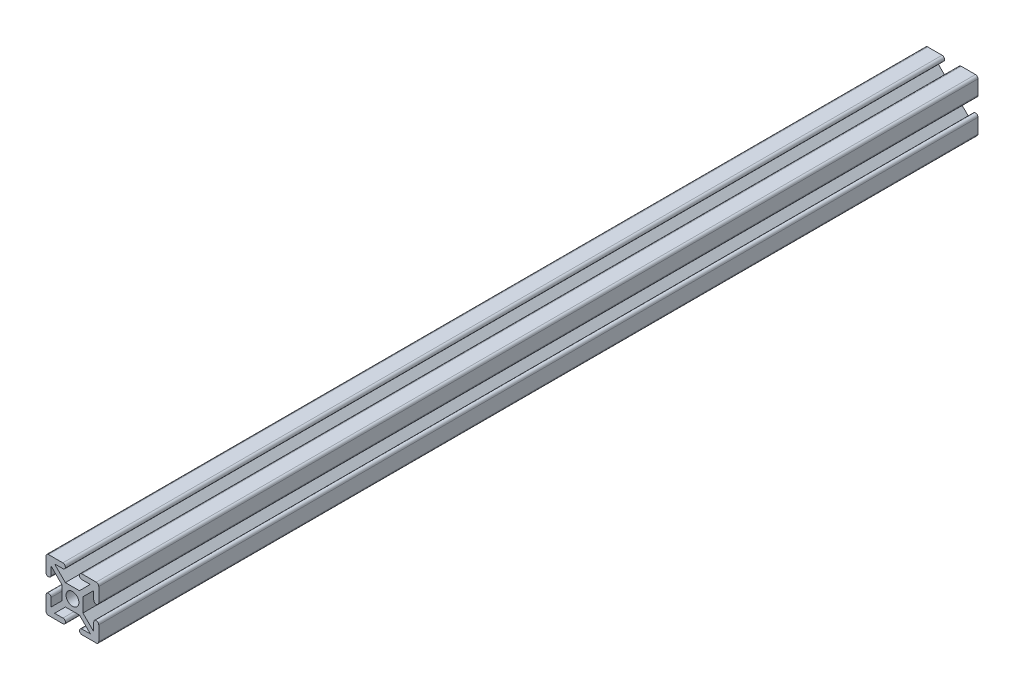
SolidWorks part; units mm, degrees
material "Aleación 6061"
ref_plane "Alzado" through (0, 0, 0) normal (0, 0, 1) x (1, 0, 0)
ref_plane "Planta" through (0, 0, 0) normal (0, 1, 0) x (1, 0, 0)
ref_plane "Vista lateral" through (0, 0, 0) normal (1, 0, 0) x (0, 0, -1)
sketch "Croquis1" plane through (0, 0, 0) normal (0, 0, 1) x (1, 0, 0)
  line L0 (-6.9113, -9.1825) -> (-6.9113, -7.7575) construction
  line L1 (12.1416, -25.3325) -> (16.8666, -25.3325)
  line L2 (-8.3363, 0.3925) -> (-8.3363, -7.7575)
  line L3 (-6.9113, 1.8175) -> (1.2387, 1.8175)
  line L4 (12.0887, 1.8175) -> (20.2387, 1.8175)
  line L5 (-3.4334, -25.3325) -> (1.2916, -25.3325)
  line L6 (0.6637, -9.1825) -> (0.6637, -17.1825)
  line L7 (-8.2834, -18.6075) -> (-8.2834, -26.7575)
  line L8 (-6.8849, -28.1561) -> (1.2916, -28.1825)
  line L9 (21.6637, 0.3925) -> (21.6637, -7.6538)
  line L10 (-5.4863, -3.0325) -> (-5.4863, -7.7575)
  line L11 (21.6637, -18.5038) -> (21.6637, -26.7575)
  line L12 (2.6637, 0.3925) -> (1.2387, 0.3925) construction
  line L13 (12.1416, -28.1825) -> (20.2387, -28.1825)
  line L14 (-3.4863, -1.0325) -> (1.2387, -1.0325)
  line L15 (-5.4863, -18.6075) -> (-5.4863, -23.3325)
  line L16 (10.6637, 0.3925) -> (12.0887, 0.3925) construction
  line L17 (12.0887, -1.0325) -> (16.8137, -1.0325)
  line L18 (20.2387, -9.0788) -> (20.2387, -7.6538) construction
  line L19 (2.6637, -7.1825) -> (-3.4863, -1.0325)
  line L20 (18.8137, -3.0325) -> (18.8137, -7.6538)
  line L21 (20.2387, -17.0788) -> (20.2387, -18.5038) construction
  line L22 (0.6637, -9.1825) -> (-5.4863, -3.0325)
  line L23 (18.8137, -18.5038) -> (18.8137, -23.3325)
  line L24 (10.7166, -26.7575) -> (12.1416, -26.7575) construction
  line L25 (0.6637, -17.1825) -> (-5.4863, -23.3325)
  line L26 (2.6637, -7.1825) -> (10.6637, -7.1825)
  line L27 (10.6637, -7.1825) -> (16.8137, -1.0325)
  line L28 (-6.8849, -17.1825) -> (-6.8849, -18.6075) construction
  line L29 (-3.4334, -25.3325) -> (2.7166, -19.1825)
  line L30 (2.7166, -19.1825) -> (10.7166, -19.1825)
  line L31 (10.7166, -19.1825) -> (16.8666, -25.3325)
  line L32 (2.7166, -26.7575) -> (1.2916, -26.7575) construction
  line L33 (12.6637, -17.1825) -> (18.8137, -23.3325)
  line L34 (12.6637, -9.1825) -> (18.8137, -3.0325)
  line L35 (12.6637, -9.1825) -> (12.6637, -17.1825)
  circle A0 centre (6.7166, -13.1825) radius 3.645
  arc A1 (-8.3363, -7.7575) -> (-5.4863, -7.7575) centre (-6.9113, -7.7575) ccw
  arc A2 (1.2387, -1.0325) -> (1.2387, 1.8175) centre (1.2387, 0.3925) ccw
  arc A3 (12.0887, 1.8175) -> (12.0887, -1.0325) centre (12.0887, 0.3925) ccw
  arc A4 (18.8137, -7.6538) -> (21.6637, -7.6538) centre (20.2387, -7.6538) ccw
  arc A5 (21.6637, -18.5038) -> (18.8137, -18.5038) centre (20.2387, -18.5038) ccw
  arc A6 (12.1416, -25.3325) -> (12.1416, -28.1825) centre (12.1416, -26.7575) ccw
  arc A7 (-5.4863, -18.6075) -> (-8.2834, -18.6075) centre (-6.8849, -18.6075) ccw
  arc A8 (1.2916, -28.1825) -> (1.2916, -25.3325) centre (1.2916, -26.7575) ccw
  arc A9 (-8.2834, -26.7575) -> (-6.8849, -28.1561) centre (-6.8849, -26.7575) ccw
  arc A10 (20.2387, -28.1825) -> (21.6637, -26.7575) centre (20.2387, -26.7575) ccw
  arc A11 (21.6637, 0.3925) -> (20.2387, 1.8175) centre (20.2387, 0.3925) ccw
  arc A12 (-6.9113, 1.8175) -> (-8.3363, 0.3925) centre (-6.9113, 0.3925) ccw
  dimension "D1" = 7.29
  dimension "D2" = 1.425
  dimension "D3" = 1.425
  dimension "D4" = 1.425
  dimension "D5" = 1.425
  dimension "D6" = 1.425
  dimension "D7" = 1.425
  dimension "D8" = 1.425
  dimension "D9" = 1.425
extrude "Saliente-Extruir1" add sketch "Croquis1" along normal blind 500
